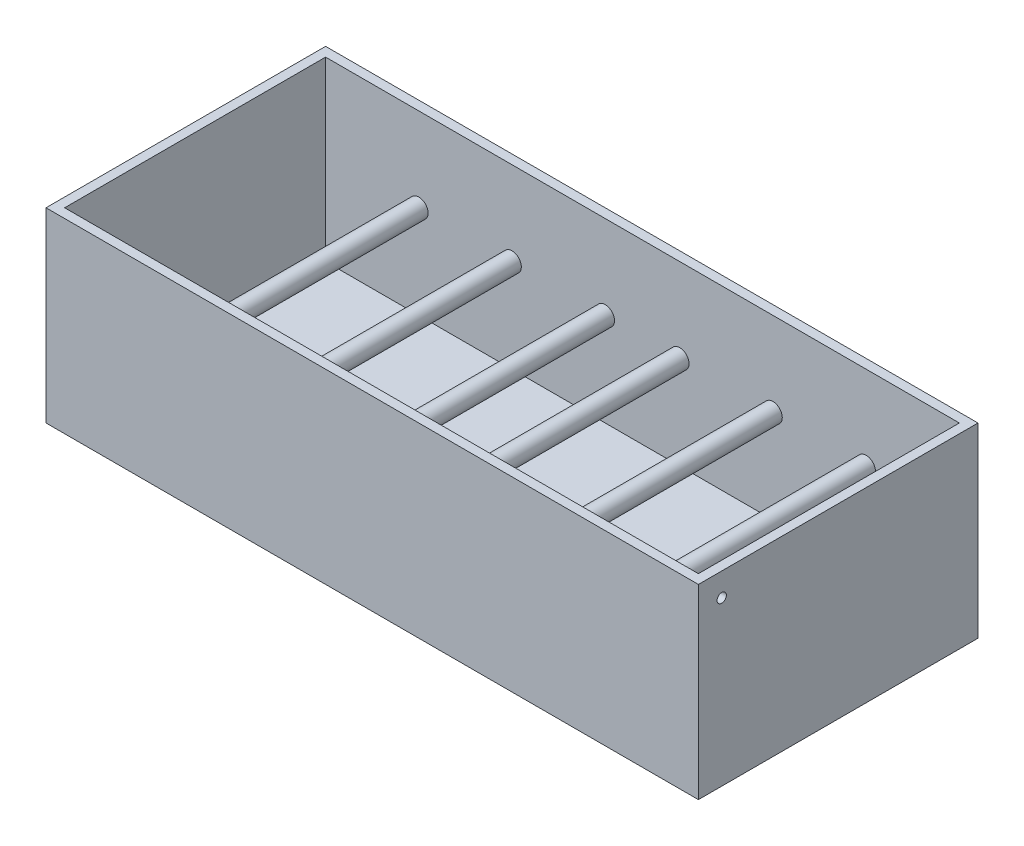
SolidWorks part; units mm, degrees
ref_plane "Alzado" through (0, 0, 0) normal (0, 0, 1) x (1, 0, 0)
ref_plane "Planta" through (0, 0, 0) normal (0, 1, 0) x (1, 0, 0)
ref_plane "Vista lateral" through (0, 0, 0) normal (1, 0, 0) x (0, 0, -1)
sketch "Croquis1" plane through (0, 0, 0) normal (0, 1, 0) x (1, 0, 0)
  line L1 (-350, -150) -> (350, -150)
  line L2 (-350, -150) -> (-350, 150)
  line L3 (-350, 150) -> (350, 150)
  line L4 (350, -150) -> (350, 150)
  line L5 (-350, -150) -> (350, 150) construction
  line L6 (-350, 150) -> (350, -150) construction
  point P1 (0, 0)
  dimension "D1" = 700
  dimension "D2" = 300
extrude "Saliente-Extruir1" add sketch "Croquis1" along normal blind 200
sketch "Croquis2" plane through (0, 200, 0) normal (0, 1, 0) x (1, 0, 0)
  line L1 (-340, -140) -> (340, -140)
  line L2 (-340, -140) -> (-340, 140)
  line L3 (-340, 140) -> (340, 140)
  line L4 (340, -140) -> (340, 140)
  line L5 (-340, -140) -> (340, 140) construction
  line L6 (-340, 140) -> (340, -140) construction
  point P0 (0, 0)
  dimension "D1" = 680
  dimension "D2" = 280
extrude "Cortar-Extruir1" cut sketch "Croquis2" against normal blind 190
sketch "Croquis3" plane through (350, 0, 0) normal (1, 0, 0) x (0, 0, -1)
  line L0 (-150, 200) -> (150, 200) construction
  line L1 (-150, 200) -> (-150, 0) construction
  circle A0 centre (-125, 175) radius 5
  dimension "D1" = 25
  dimension "D2" = 25
extrude "Cortar-Extruir2" cut sketch "Croquis3" against normal blind 700
sketch "Croquis4" plane through (0, 0, 140) normal (0, 0, -1) x (-1, 0, 0)
  line L0 (-340, 10) -> (-340, 200) construction
  line L1 (340, 10) -> (340, 200) construction
  line L2 (340, 10) -> (-340, 10) construction
  circle A0 centre (-240, 110) radius 10
  circle A1 centre (-140, 110) radius 10
  circle A2 centre (-40, 110) radius 10
  circle A3 centre (140, 110) radius 10
  circle A4 centre (240, 110) radius 10
  circle A5 centre (40, 110) radius 10
  dimension "D5" = 100
  dimension "D6" = 100
  dimension "D1" = 100
  dimension "D2" = 100
  dimension "D3" = 100
  dimension "D4" = 100
  dimension "D7" = 100
  dimension "D8" = 100
extrude "Saliente-Extruir2" add sketch "Croquis4" along normal up to surface (280 mm away) up to face at (0, 105, -140)
